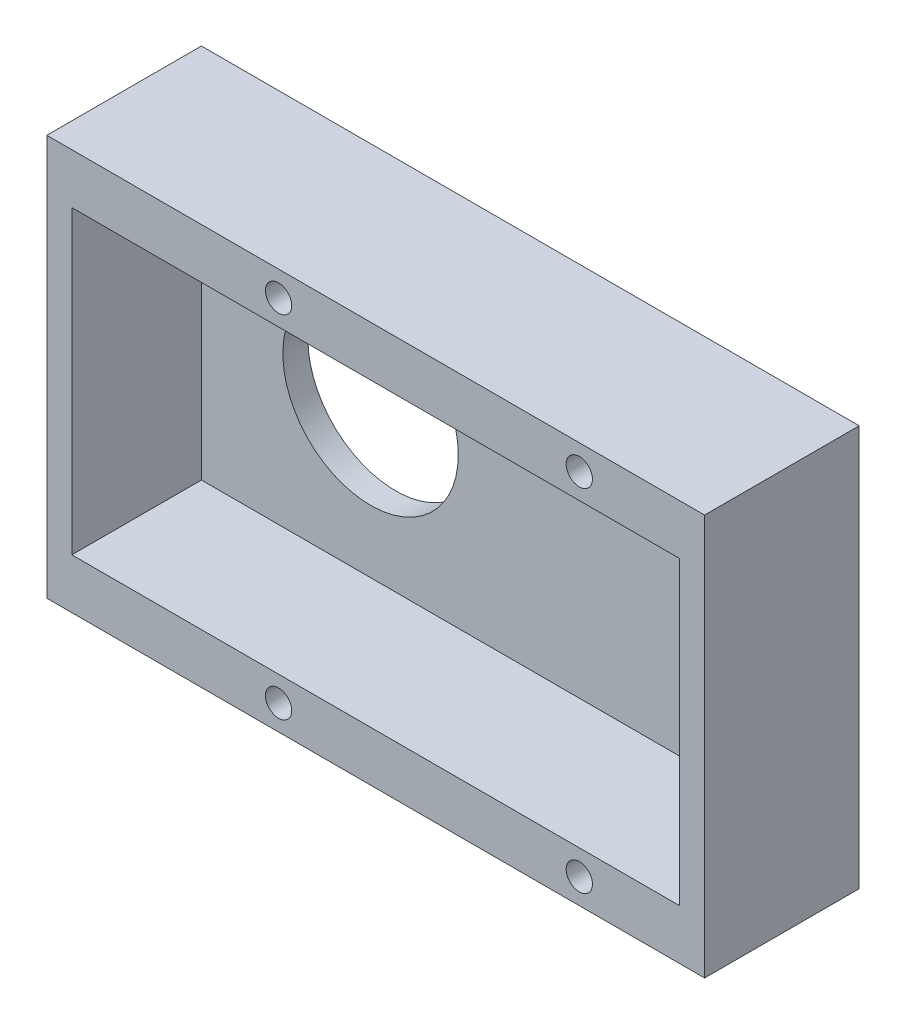
SolidWorks part; units mm, degrees
ref_plane "前视基准面" through (0, 0, 0) normal (0, 0, 1) x (1, 0, 0)
ref_plane "上视基准面" through (0, 0, 0) normal (0, 1, 0) x (1, 0, 0)
ref_plane "右视基准面" through (0, 0, 0) normal (1, 0, 0) x (0, 0, -1)
other "Configuration Table"
sketch "草图1" plane through (0, 0, 0) normal (0, 0, 1) x (1, 0, 0)
  line L1 (0, 0) -> (52.5, 0)
  line L2 (0, 0) -> (0, 32)
  line L3 (0, 32) -> (52.5, 32)
  line L4 (52.5, 0) -> (52.5, 32)
  dimension "D1" = 32
  dimension "D2" = 52.5
extrude "凸台-拉伸1" add sketch "草图1" along normal blind 2
sketch "草图2" plane through (0, 0, 2) normal (0, 0, 1) x (1, 0, 0)
  line L1 (0, 32) -> (52.5, 32)
  line L2 (0, 32) -> (0, 0)
  line L3 (0, 0) -> (52.5, 0)
  line L4 (52.5, 32) -> (52.5, 0)
  line L5 (2, 28) -> (50.5, 28)
  line L6 (2, 28) -> (2, 4)
  line L7 (2, 4) -> (50.5, 4)
  line L8 (50.5, 28) -> (50.5, 4)
  dimension "D1" = 4
  dimension "D2" = 2
  dimension "D3" = 4
  dimension "D4" = 2
extrude "凸台-拉伸2" add sketch "草图2" along normal blind 10.34
sketch "草图3" plane through (0, 0, 2) normal (0, 0, 1) x (1, 0, 0)
  line L0 (2, 16) -> (34.9442, 16) construction
  line L1 (2, 28) -> (2, 4) construction
  circle A0 centre (15.5, 16) radius 7
  dimension "D1" = 14
  dimension "D2" = 13.5
extrude "切除-拉伸1" cut sketch "草图3" against normal up to next
sketch "草图4" plane through (0, 0, 12.34) normal (0, 0, 1) x (1, 0, 0)
  line L0 (30.5, 28) -> (30.5, 4) construction
  line L3 (50.5, 16) -> (2, 16) construction
  line L4 (50.5, 4) -> (50.5, 28) construction
  line L5 (2, 28) -> (2, 4) construction
  line L6 (50.5, 4) -> (50.5, 28) construction
  circle A0 centre (18.5, 30) radius 1.05
  circle A1 centre (42.5, 30) radius 1.05
  circle A2 centre (42.5, 2) radius 1.05
  circle A3 centre (18.5, 2) radius 1.05
  dimension "D1" = 2.1
  dimension "D2" = 28
  dimension "D3" = 24
  dimension "D4" = 20
extrude "切除-拉伸2" cut sketch "草图4" against normal up to next
